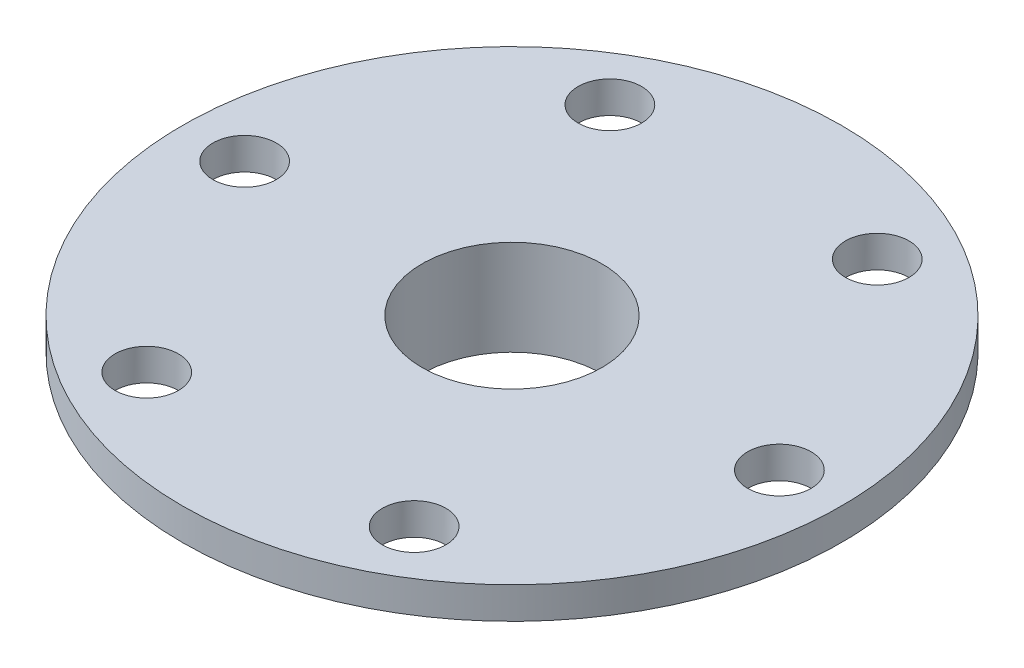
SolidWorks part; units mm, degrees
material "1060 Alloy"
ref_plane "Front Plane" through (0, 0, 0) normal (0, 0, 1) x (1, 0, 0)
ref_plane "Top Plane" through (0, 0, 0) normal (0, 1, 0) x (1, 0, 0)
ref_plane "Right Plane" through (0, 0, 0) normal (1, 0, 0) x (0, 0, -1)
sketch "Sketch4" plane through (0, 0, 0) normal (0, 0, 1) x (1, 0, 0)
  line L0 (0, 27.2792) -> (0, -44.2975) construction
  line L1 (-8.5, 0) -> (-31.1438, 0)
  line L2 (-31.1438, 0) -> (-31.1438, -3)
  line L3 (-31.1438, -3) -> (-12.25, -3)
  line L4 (-12.25, -3) -> (-12.25, -9)
  line L5 (-12.25, -9) -> (-8.5, -9)
  line L6 (-8.5, -9) -> (-8.5, 0)
  line L7 (0, 15) -> (-38.0375, 15) construction
  line L8 (0, 20) -> (-12.5, 20) construction
  line L9 (-12.5, 20) -> (-38.0375, 15) construction
  line L10 (-25.2688, 17.5) -> (-25.2688, 15) construction
  dimension "D2" = 3
  dimension "D3" = 8.5
  dimension "D4" = 12.25
  dimension "D5" = 6
  dimension "D6" = 15
  dimension "D7" = 38.0375
  dimension "D8" = 12.5
  dimension "D9" = 5
  dimension "D1" = 5.875
revolve "Revolve1" add sketch "Sketch4" angle 360 about L0
sketch "Sketch5" plane through (0, 0, 0) normal (0, 1, 0) x (1, 0, 0)
  line L0 (-12.5, 0) -> (-38.0375, 0) construction
  circle A0 centre (0, 0) radius 25.2688 construction
  circle A1 centre (-25.2688, 0) radius 3
  circle A2 centre (-12.6344, 21.8834) radius 3
  circle A3 centre (12.6344, 21.8834) radius 3
  circle A4 centre (25.2688, 0) radius 3
  circle A5 centre (12.6344, -21.8834) radius 3
  circle A6 centre (-12.6344, -21.8834) radius 3
  circle A7 centre (0, 0) radius 12.5 construction
  circle A9 centre (0, 0) radius 38.0375 construction
  point P17 (0, 0)
  dimension "D2" = 6
  dimension "D3" = 25
  dimension "D4" = 76.075
  dimension "D1" = 6
extrude "Cut-Extrude1" cut sketch "Sketch5" against normal through all
equation "\"Stator_OD\"= 60'No Tolerance given"
equation "\"A\"=35.81 'taken off spec sheet for 06808 (A)"
equation "\"Rotor_ID\"= 30'No Tolerance Given"
equation "\"back_bearing_Thickness\"= 8'randomish, thinnest off mcmaster"
equation "\"back_bearing_OD\"= 25'currently non-sense"
equation "\"Stator_Gap\"= 0.0375'+- 0.0125 (From 1.3.3.1 Kollmorgen manual)"
equation "\"Back_mount_hole\"= 1.75'To be tapped to M2 (USE LOCKTITE)"
equation "\"facePlate_Mount_Hole\"= 5.75'To be tapped to M6"
equation "\"final_shaftD\"= 8'NEMA 23 shaft diameter. Should fit with harmonic?"
equation "\"final_shaftL\"= 50'random length. Idk"
equation "\"back_bearing_ID\"= 15'Random number"
equation "\"back_bearing_IDOD\"= 18'Random number, OD of the inner bearing ring"
equation "\"rotor_shaftD\"= \"Rotor_ID\" - (\"rotor-shaft_gap\")*2'"
equation "\"front_bearing_ID\"= 12'random"
equation "\"front_bearing_OD\"= 20'random"
equation "\"front_bearing_IDOD\"= 14'random"
equation "\"front_bearing_Thickness\"= 5'randomish, thinnest off mcmaster"
equation "\"rotor_thickness\"= 2.4'measured off CAD"
equation "\"rotor_height\"= 32.86'+-0.075 taken off spec sheet for 06826 (C)"
equation "\"B\"= 26.3'+-0.35 taken off spec sheet for 06826"
equation "\"D3@Sketch4\" = \"back_bearing_ID\" / 2 + 1"
equation "\"D4@Sketch4\"=\"back_bearing_OD\"/2-0.25"
equation "\"D3@Sketch5\"=\"back_bearing_OD\""
equation "\"D4@Sketch5\"=\"Stator_OD\"+\"Stator_Gap\"*2+16"
equation "\"D7@Sketch4\"=\"Stator_OD\"/2+\"Stator_Gap\"+8"
equation "\"D8@Sketch4\"=\"back_bearing_OD\"/2"
equation "\"D2@Sketch5\"=\"facePlate_Mount_Hole\"+0.25"
equation "\"D1@Sketch4\"=\"facePlate_Mount_Hole\"/2+3"
